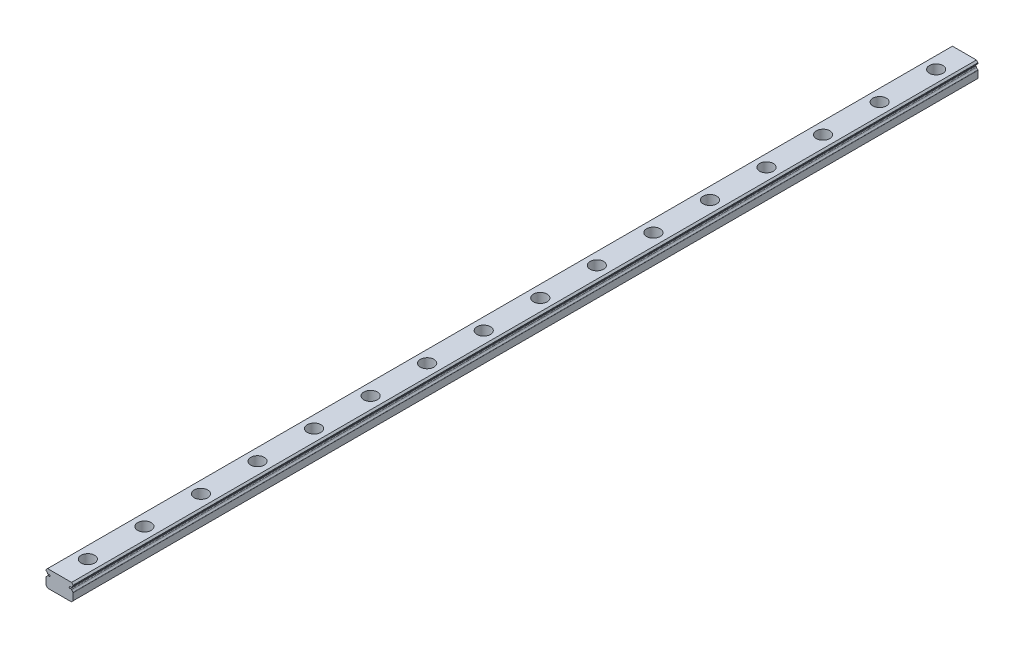
SolidWorks part; units mm, degrees
ref_plane "Front Plane" through (0, 0, 0) normal (0, 0, 1) x (1, 0, 0)
ref_plane "Top Plane" through (0, 0, 0) normal (0, 1, 0) x (1, 0, 0)
ref_plane "Right Plane" through (0, 0, 0) normal (1, 0, 0) x (0, 0, -1)
other "Configuration Table"
sketch "Sketch4" plane through (0, 0, 0) normal (0, 0, 1) x (1, 0, 0)
  line L1 (-6, -7.5) -> (6, -7.5)
  line L2 (-6, -7.5) -> (-6, 0)
  line L3 (-6, 0) -> (6, 0)
  line L4 (6, -7.5) -> (6, 0)
  line L5 (-6, -7.5) -> (6, 0) construction
  line L6 (-6, 0) -> (6, -7.5) construction
  point P0 (0, -3.75)
  dimension "D1" = 12
  dimension "D2" = 7.5
extrude "Boss-Extrude1" add sketch "Sketch4" along normal blind 400
sketch "Sketch5" plane through (0, 0, 0) normal (0, 0, 1) x (1, 0, 0)
  line L0 (-6, -7.5) -> (-6, 0) construction
  line L1 (-6, 0) -> (6, 0) construction
  line L2 (-6, 0) -> (-6, -7.5) construction
  arc A2 (-5.3293, -1.8875) -> (-5.3293, -2.7125) centre (-6.5884, -2.3) ccw
  arc A3 (-4.9276, -1.9982) -> (-4.9276, -2.6018) centre (-4.665, -2.3) cw
  arc A4 (-4.9276, -2.6018) -> (-5.3293, -2.7125) centre (-5.0917, -2.7904) ccw
  arc A5 (-4.9276, -1.9982) -> (-5.3293, -1.8875) centre (-5.0917, -1.8096) cw
  dimension "D2" = 1.325
  dimension "D3" = 0.5884
  dimension "D1" = 0.4
  dimension "D6" = 0.25
  dimension "D4" = 1.335
  dimension "D5" = 2.3
extrude "Cut-Extrude1" cut sketch "Sketch5" along normal through all
mirror "Mirror3" about plane through (0, 0, 0) normal (1, 0, 0) of "Cut-Extrude1"
fillet "Fillet1" radius 0.2 4 edges at (-6, -3.4872, 200) (-6, -1.1128, 200) (6, -1.1128, 200) (6, -3.4872, 200)
chamfer "Chamfer1" distance 0.7 angle 45 2 edges at (-6, 0, 200) (6, 0, 200)
chamfer "Chamfer2" distance 0.8 angle 45 2 edges at (-6, -7.5, 200) (6, -7.5, 200)
sketch "Sketch7" plane through (0, 0, 0) normal (0, 1, 0) x (1, 0, 0)
  point P0 (0, -12.5)
  dimension "D1" = 12.5
hole_wizard "CBORE for M3 Hex Socket Head Cap Screw1" positions "Sketch7" profile "Sketch8" counterbore size "M3" standard "DIN" end condition through all
sketch "Sketch8" plane through (0, 0, 12.5) normal (1, 0, 0) x (0, 0, 1)
  line L0 (0, 0) -> (0, 7.5)
  line L1 (0, 7.5) -> (1.75, 7.5)
  line L3 (1.75, 7.5) -> (1.75, 4.4)
  line L4 (1.75, 4.4) -> (3, 4.4)
  line L5 (3, 4.4) -> (3, 0)
  line L7 (3, 0) -> (0, 0)
  line L11 (0, -6.35) -> (0, 107.95) construction
  dimension "Thru Hole Dia." = 3.5
  dimension "Thru Hole Depth" = 7.5
  dimension "C'Bore Dia." = 6
  dimension "C'Bore Depth" = 4.4
pattern_linear "LPattern1" count 16 spacing 25 along (0, 0, 1) of "CBORE for M3 Hex Socket Head Cap Screw1"
